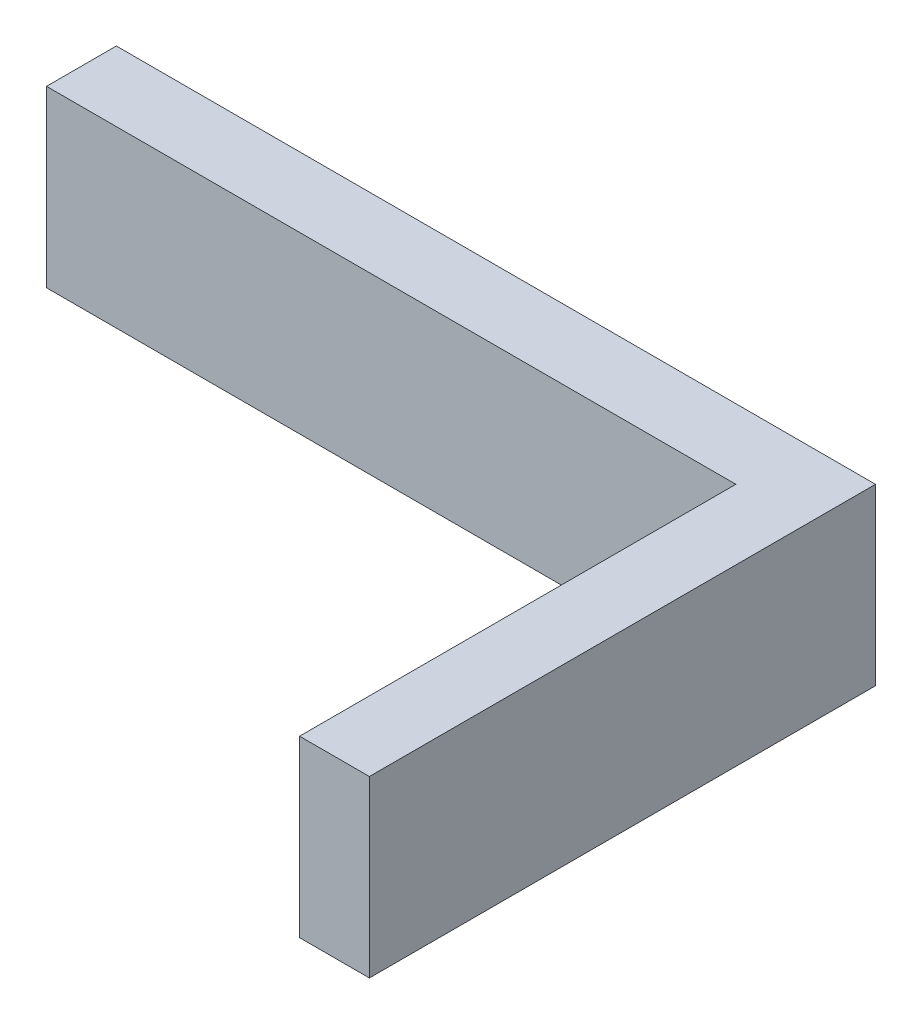
SolidWorks part; units mm, degrees
ref_plane "Front Plane" through (0, 0, 0) normal (0, 0, 1) x (1, 0, 0)
ref_plane "Top Plane" through (0, 0, 0) normal (0, 1, 0) x (1, 0, 0)
ref_plane "Right Plane" through (0, 0, 0) normal (1, 0, 0) x (0, 0, -1)
sketch "Sketch1" plane through (0, 0, 0) normal (0, 0, 1) x (1, 0, 0)
  line L1 (0, 0) -> (43.5, 0)
  line L2 (0, 0) -> (0, 10)
  line L3 (0, 10) -> (43.5, 10)
  line L4 (43.5, 0) -> (43.5, 10)
  dimension "D1" = 43.5
  dimension "D2" = 10
extrude "Boss-Extrude1" add sketch "Sketch1" along normal blind 4
sketch "Sketch2" plane through (0, 0, 4) normal (0, 0, 1) x (1, 0, 0)
  line L0 (0, 0) -> (43.5, 0) construction
  line L1 (43.5, 10) -> (39.5, 10)
  line L2 (43.5, 10) -> (43.5, 0)
  line L3 (43.5, 0) -> (39.5, 0)
  line L4 (39.5, 10) -> (39.5, 0)
  dimension "D1" = 4
extrude "Boss-Extrude2" add sketch "Sketch2" along normal blind 25
